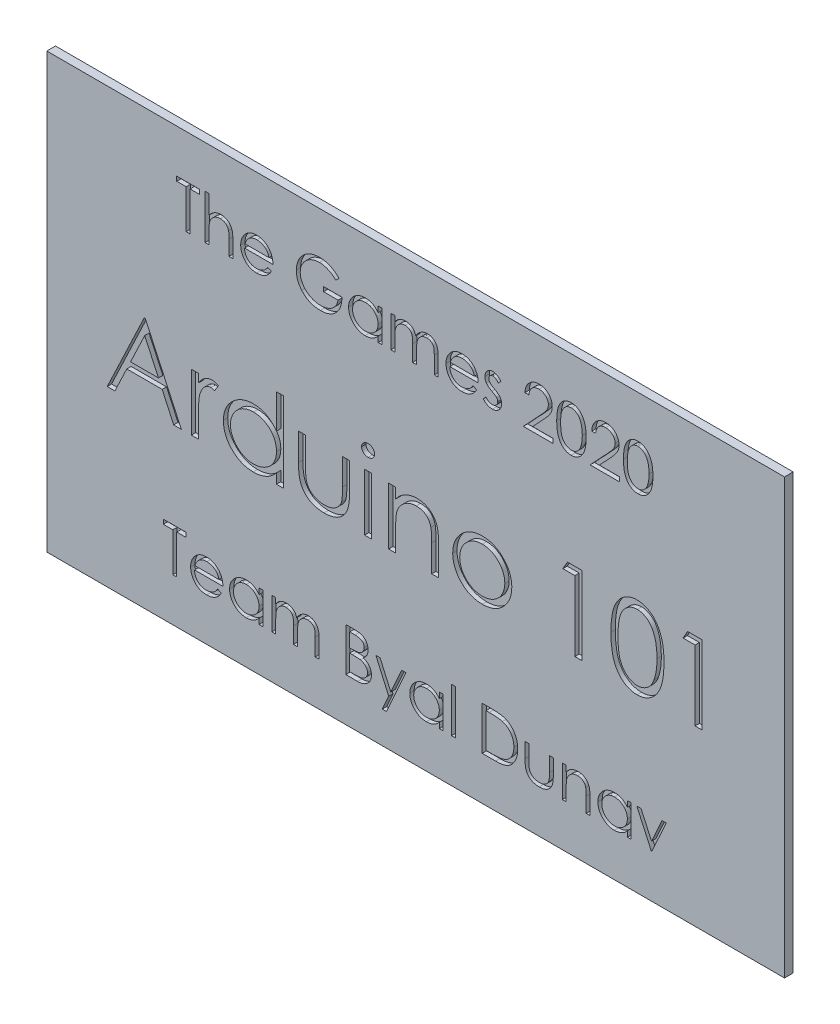
SolidWorks part; units mm, degrees
ref_plane "Front Plane" through (0, 0, 0) normal (0, 0, 1) x (1, 0, 0)
ref_plane "Top Plane" through (0, 0, 0) normal (0, 1, 0) x (1, 0, 0)
ref_plane "Right Plane" through (0, 0, 0) normal (1, 0, 0) x (0, 0, -1)
sketch "Sketch2" plane through (0, 0, 0) normal (0, 0, 1) x (1, 0, 0)
  line L1 (425, -250) -> (-425, -250)
  line L2 (425, -250) -> (425, 250)
  line L3 (425, 250) -> (-425, 250)
  line L4 (-425, -250) -> (-425, 250)
  line L5 (425, -250) -> (-425, 250) construction
  line L6 (425, 250) -> (-425, -250) construction
  point P0 (0, 0)
  dimension "D1" = 500
  dimension "D2" = 850
extrude "Boss-Extrude1" add sketch "Sketch2" along normal blind 10
sketch "Sketch3" plane through (0, 0, 0) normal (0, 0, -1) x (-1, 0, 0)
  line L1 (350, -175) -> (-350, -175) construction
  line L2 (350, -175) -> (350, 175) construction
  line L3 (350, 175) -> (-350, 175) construction
  line L4 (-350, -175) -> (-350, 175) construction
  line L5 (350, -175) -> (-350, 175) construction
  line L6 (350, 175) -> (-350, -175) construction
  line L7 (425, 250) -> (425, -250) construction
  circle A0 centre (-350, 175) radius 20
  circle A1 centre (350, 175) radius 20
  circle A2 centre (350, -175) radius 20
  circle A3 centre (-350, -175) radius 20
  point P0 (0, 0)
  dimension "D4" = 40
  dimension "D5" = 40
  dimension "D6" = 40
  dimension "D7" = 40
  dimension "D1" = 350
  dimension "D2" = 700
  dimension "D3" = 75
extrude "Boss-Extrude2" add sketch "Sketch3" along normal blind 30
sketch "Sketch4" plane through (0, 0, 10) normal (0, 0, 1) x (1, 0, 0)
  line L0 (-425, -200) -> (425, -200) construction
  line L1 (-425, 250) -> (-425, -250) construction
  line L2 (425, -250) -> (425, 250) construction
  line L3 (425, 250) -> (-425, 250) construction
  line L4 (-425, 150) -> (425, 150) construction
  line L5 (-425, -250) -> (425, -250) construction
  line L6 (-425, -50) -> (425, -50) construction
  text T0 "Team Byal Dunav" font "Century Gothic" height 50
  text T1 "The Games 2020" font "Century Gothic" height 50
  text T2 "Arduino 101" font "Century Gothic" height 90
  dimension "D1" = 50
  dimension "D2" = 100
  dimension "D3" = 300
extrude "Cut-Extrude3" cut sketch "Sketch4" against normal blind 5
